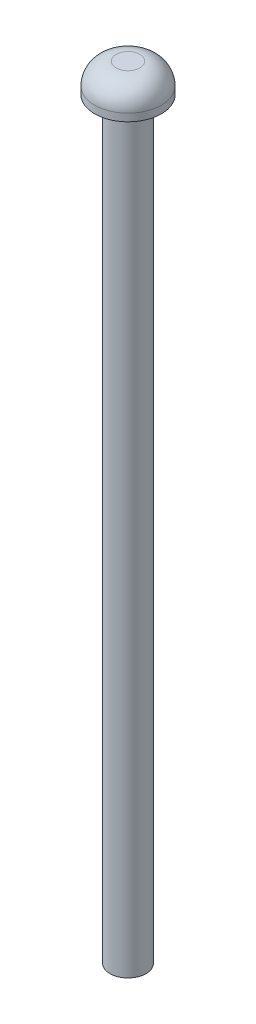
SolidWorks part; units mm, degrees
ref_plane "Alzado" through (0, 0, 0) normal (0, 0, 1) x (1, 0, 0)
ref_plane "Planta" through (0, 0, 0) normal (0, 1, 0) x (1, 0, 0)
ref_plane "Vista lateral" through (0, 0, 0) normal (1, 0, 0) x (0, 0, -1)
sketch "Croquis1" plane through (0, 0, 0) normal (0, 1, 0) x (1, 0, 0)
  circle A0 centre (0, 0) radius 1.675
  dimension "D1" = 3.35
extrude "Saliente-Extruir1" add sketch "Croquis1" against normal blind 70
sketch "Croquis2" plane through (0, 0, 0) normal (0, 1, 0) x (1, 0, 0)
  circle A0 centre (0, 0) radius 3.1
  dimension "D1" = 6.2
extrude "Saliente-Extruir2" add sketch "Croquis2" along normal blind 2.7
fillet "Redondeo1" radius 2 1 edges at (0, 2.7, 3.1)
